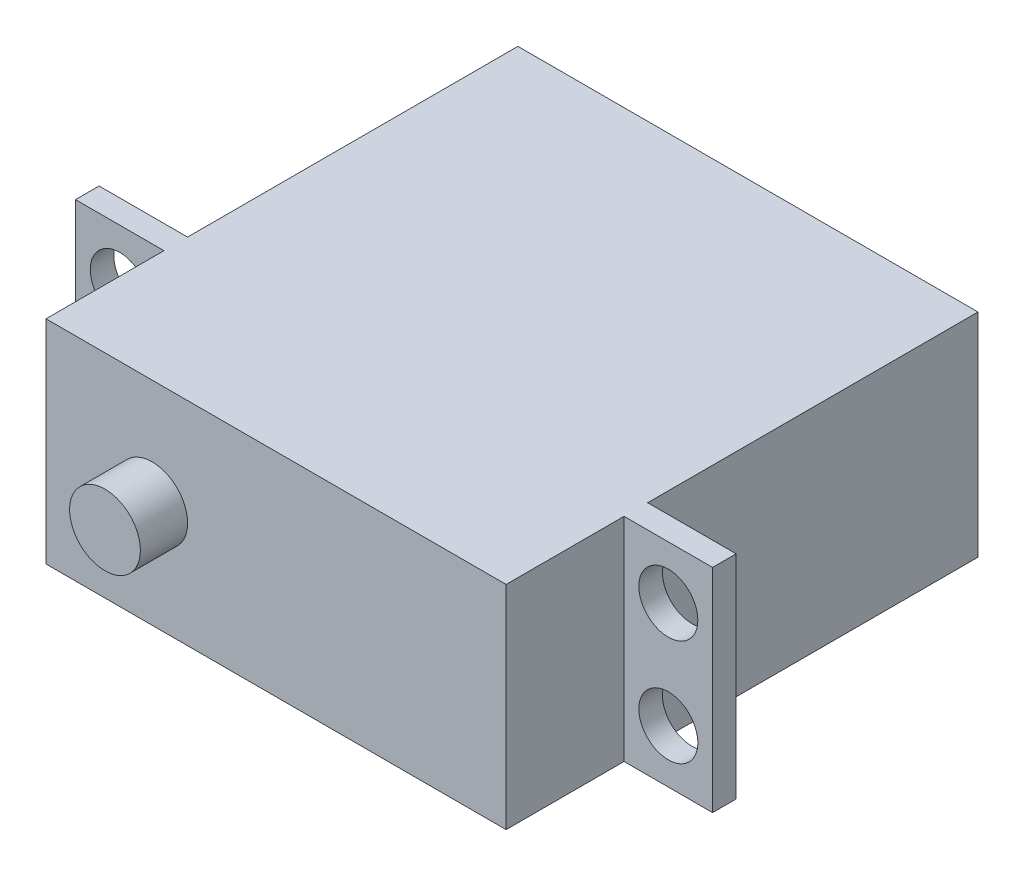
SolidWorks part; units mm, degrees
ref_plane "前视基准面" through (0, 0, 0) normal (0, 0, 1) x (1, 0, 0)
ref_plane "上视基准面" through (0, 0, 0) normal (0, 1, 0) x (1, 0, 0)
ref_plane "右视基准面" through (0, 0, 0) normal (1, 0, 0) x (0, 0, -1)
sketch "草图1" plane through (0, 0, 0) normal (0, 0, 1) x (1, 0, 0)
  line L1 (-27, -9) -> (27, -9)
  line L2 (-27, -9) -> (-27, 9)
  line L3 (-27, 9) -> (27, 9)
  line L4 (27, -9) -> (27, 9)
  line L5 (-27, -9) -> (27, 9) construction
  line L6 (-27, 9) -> (27, -9) construction
  point P0 (0, 0)
  dimension "D1" = 54
  dimension "D2" = 18
extrude "凸台-拉伸1" add sketch "草图1" along normal blind 2
sketch "草图2" plane through (0, 0, 2) normal (0, 0, 1) x (1, 0, 0)
  line L0 (-27, -9) -> (27, -9) construction
  line L1 (-19.5, 9) -> (19.5, 9)
  line L2 (-19.5, 9) -> (-19.5, -9)
  line L3 (-19.5, -9) -> (19.5, -9)
  line L4 (19.5, 9) -> (19.5, -9)
  line L5 (-19.5, 9) -> (19.5, -9) construction
  line L6 (-19.5, -9) -> (19.5, 9) construction
  point P0 (0, 0)
  dimension "D1" = 39
extrude "凸台-拉伸2" add sketch "草图2" along normal blind 10
sketch "草图3" plane through (0, 0, 12) normal (0, 0, 1) x (1, 0, 0)
  line L0 (-19.5, 9) -> (-19.5, -9) construction
  circle A0 centre (-10.5, 0) radius 6 construction
  circle A1 centre (-10.5, 0) radius 3
  dimension "D1" = 12
  dimension "D2" = 9
  dimension "D3" = 6
extrude "凸台-拉伸3" add sketch "草图3" along normal blind 4
sketch "草图4" plane through (0, 0, 0) normal (0, 0, -1) x (-1, 0, 0)
  line L1 (-19.5, -9) -> (19.5, -9)
  line L2 (-19.5, -9) -> (-19.5, 9)
  line L3 (-19.5, 9) -> (19.5, 9)
  line L4 (19.5, -9) -> (19.5, 9)
  line L5 (-19.5, -9) -> (19.5, 9) construction
  line L6 (-19.5, 9) -> (19.5, -9) construction
  point P0 (0, 0)
extrude "凸台-拉伸4" add sketch "草图4" along normal blind 28
sketch "草图6" plane through (0, 0, 2) normal (0, 0, 1) x (1, 0, 0)
  line L0 (27, 0) -> (19.5, 0) construction
  line L1 (27, -9) -> (27, 9) construction
  line L2 (19.5, -9) -> (19.5, 9) construction
  line L3 (27, 9) -> (19.5, 9) construction
  line L4 (0, 9) -> (0, -9) construction
  line L5 (19.5, 9) -> (-19.5, 9) construction
  line L6 (-19.5, -9) -> (19.5, -9) construction
  circle A0 centre (23.25, 4.5) radius 2.5
  circle A1 centre (23.25, -4.5) radius 2.5
  circle A2 centre (-23.25, -4.5) radius 2.5
  circle A3 centre (-23.25, 4.5) radius 2.5
  dimension "D1" = 5
  dimension "D2" = 4.5
extrude "切除-拉伸1" cut sketch "草图6" against normal through all
